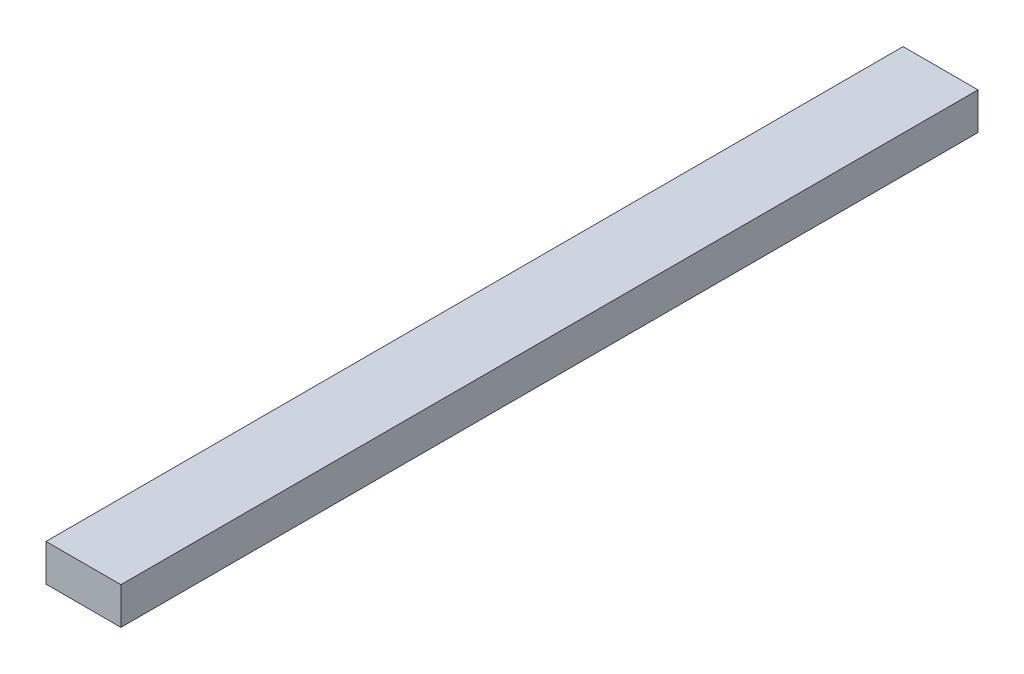
SolidWorks part; units mm, degrees
ref_plane "Front Plane" through (0, 0, 0) normal (0, 0, 1) x (1, 0, 0)
ref_plane "Top Plane" through (0, 0, 0) normal (0, 1, 0) x (1, 0, 0)
ref_plane "Right Plane" through (0, 0, 0) normal (1, 0, 0) x (0, 0, -1)
sketch "Sketch1" plane through (0, 0, 0) normal (0, 0, 1) x (1, 0, 0)
  line L1 (-6.075, -3) -> (6.075, -3)
  line L2 (-6.075, -3) -> (-6.075, 3)
  line L3 (-6.075, 3) -> (6.075, 3)
  line L4 (6.075, -3) -> (6.075, 3)
  line L5 (-6.075, -3) -> (6.075, 3) construction
  line L6 (-6.075, 3) -> (6.075, -3) construction
  point P0 (0, 0)
  dimension "D1" = 6
  dimension "D2" = 12.15
extrude "Boss-Extrude1" add sketch "Sketch1" along normal blind 139
